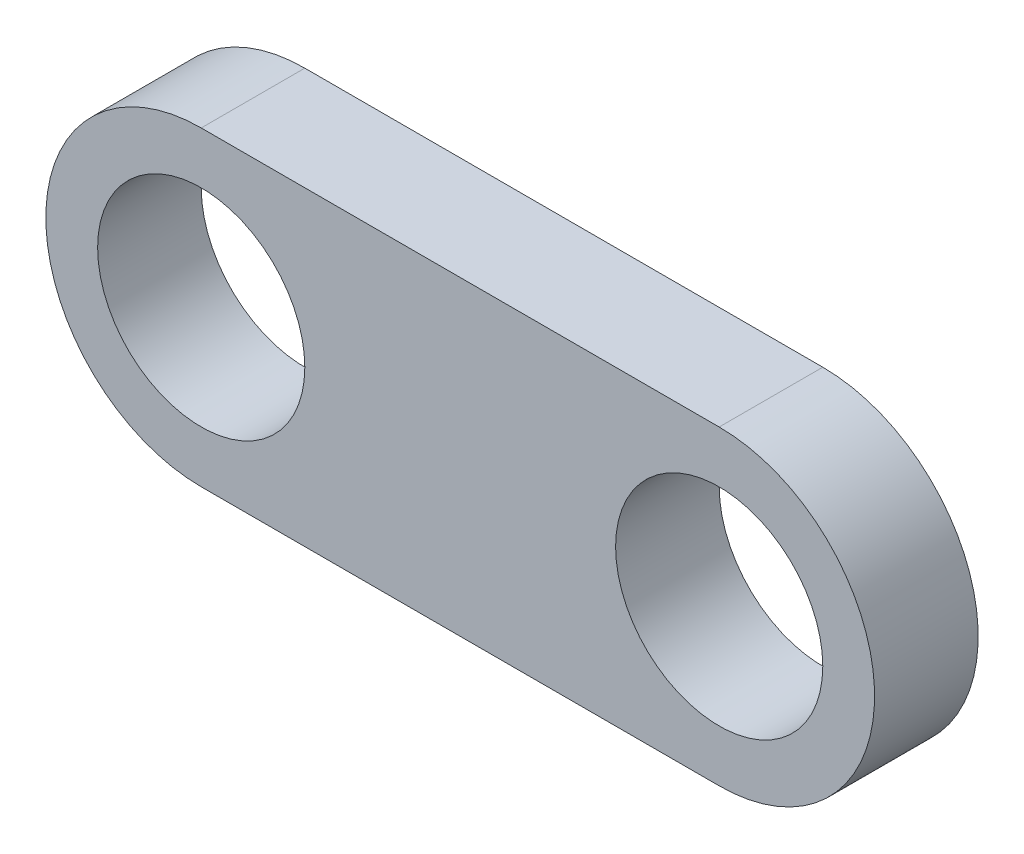
SolidWorks part; units mm, degrees
material "1.0503 (C45)"
ref_plane "Plan de face" through (0, 0, 0) normal (0, 0, 1) x (1, 0, 0)
ref_plane "Plan de dessus" through (0, 0, 0) normal (0, 1, 0) x (1, 0, 0)
ref_plane "Plan de droite" through (0, 0, 0) normal (1, 0, 0) x (0, 0, -1)
sketch "Esquisse1" plane through (0, 0, 0) normal (0, 0, 1) x (1, 0, 0)
  line L0 (0, 0) -> (-50, 0) construction
  line L1 (0, -15) -> (-50, -15)
  line L2 (0, 15) -> (-50, 15)
  arc A0 (0, -15) -> (0, 15) centre (0, 0) ccw
  arc A1 (-50, 15) -> (-50, -15) centre (-50, 0) ccw
  circle A2 centre (-50, 0) radius 10
  circle A3 centre (0, 0) radius 10
  point P3 (-25, 0)
  dimension "D1" = 20
  dimension "D2" = 50
  dimension "D3" = 30
extrude "Boss.-Extru.1" add sketch "Esquisse1" along normal mid plane 10
